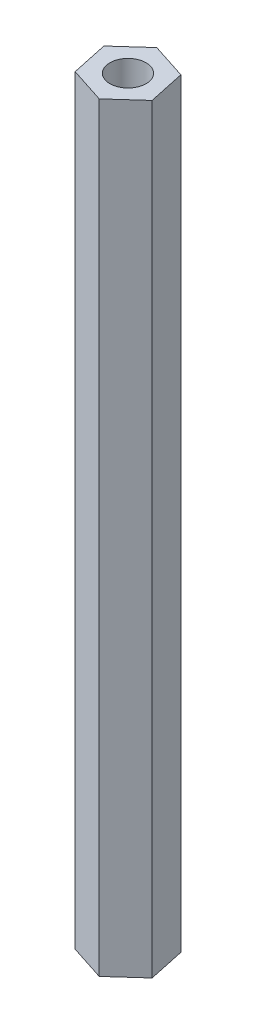
SolidWorks part; units mm, degrees
ref_plane "Plano frontal" through (0, 0, 0) normal (0, 0, 1) x (1, 0, 0)
ref_plane "Plano superior" through (0, 0, 0) normal (0, 1, 0) x (1, 0, 0)
ref_plane "Plano direito" through (0, 0, 0) normal (1, 0, 0) x (0, 0, -1)
sketch "Esboço1" plane through (0, 0, 0) normal (0, 1, 0) x (1, 0, 0)
  line L1 (3.092, -1.001) -> (2.4129, 2.1772)
  line L2 (2.4129, 2.1772) -> (-0.6791, 3.1783)
  line L3 (-0.6791, 3.1783) -> (-3.092, 1.001)
  line L4 (-3.092, 1.001) -> (-2.4129, -2.1772)
  line L5 (-2.4129, -2.1772) -> (0.6791, -3.1783)
  line L6 (0.6791, -3.1783) -> (3.092, -1.001)
  circle A0 centre (0, 0) radius 3.25 construction
extrude "Ressalto-extrusão1" add sketch "Esboço1" along normal blind 66
hole_wizard "Furo roscado para conduíte de M3x0.51" positions "Esboço2" profile "Esboço3" tap size "M3x0.5" standard "Helicoil® Metric"
sketch "Esboço2" plane through (0, 0, 0) normal (0, -1, 0) x (-1, 0, 0)
  point P0 (0, 0)
cosmetic thread "Rosca de furo1"
sketch "Esboço3" plane through (0, 0, 0) normal (1, 0, 0) x (0, 0, -1)
  line L0 (0, 0) -> (0, 10.9464)
  line L1 (0, 10.9464) -> (1.575, 10)
  line L2 (1.575, 10) -> (1.575, 0)
  line L5 (1.575, 0) -> (0, 0)
  line L10 (0, 10.9464) -> (-1.575, 10) construction
  line L11 (0, -6.35) -> (0, 107.95) construction
  dimension "Tap Drill Dia." = 3.15
  dimension "Tap Drill Depth" = 10
  dimension "Drill Angle" = 118
hole_wizard "Furo roscado para conduíte de M3x0.52" positions "Esboço5" profile "Esboço4" tap size "M3x0.5" standard "Helicoil® Metric"
sketch "Esboço5" plane through (0, 66, 0) normal (0, 1, 0) x (1, 0, 0)
  point P3 (0, 0)
sketch "Esboço4" plane through (0, 66, 0) normal (1, 0, 0) x (0, 0, 1)
  line L0 (0, 0) -> (0, 10.9464)
  line L1 (0, 10.9464) -> (1.575, 10)
  line L2 (1.575, 10) -> (1.575, 0)
  line L5 (1.575, 0) -> (0, 0)
  line L10 (0, 10.9464) -> (-1.575, 10) construction
  line L11 (0, -6.35) -> (0, 107.95) construction
  dimension "Tap Drill Dia." = 3.15
  dimension "Tap Drill Depth" = 10
  dimension "Drill Angle" = 118
cosmetic thread "Rosca de furo2" parameters "D1"=10, "D2"=3.716
